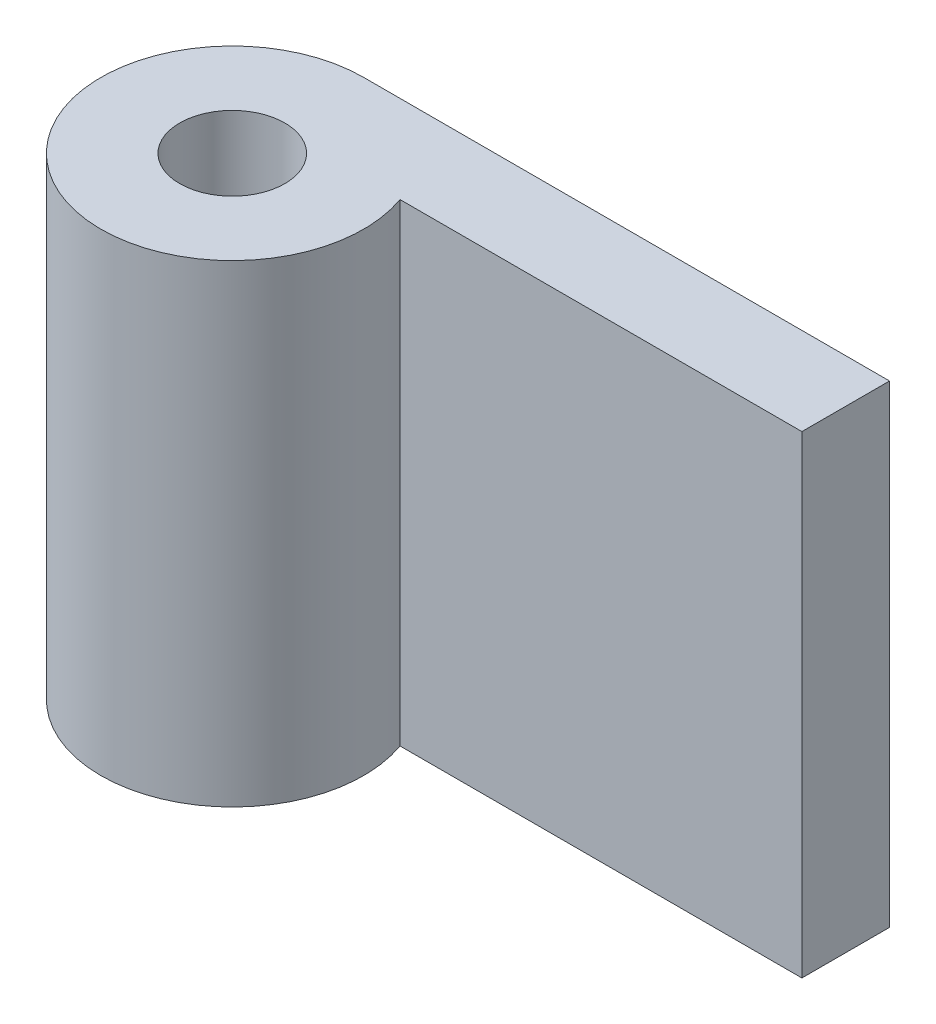
SolidWorks part; units mm, degrees
ref_plane "前视基准面" through (0, 0, 0) normal (0, 0, 1) x (1, 0, 0)
ref_plane "上视基准面" through (0, 0, 0) normal (0, 1, 0) x (1, 0, 0)
ref_plane "右视基准面" through (0, 0, 0) normal (1, 0, 0) x (0, 0, -1)
sketch "草图1" plane through (0, 0, 0) normal (0, 1, 0) x (1, 0, 0)
  circle A0 centre (0, 0) radius 3
  dimension "D1" = 6
extrude "凸台-拉伸1" add sketch "草图1" along normal blind 10.8
sketch "草图7" plane through (0, 0, 0) normal (1, 0, 0) x (0, 0, -1)
  line L0 (3, 10.8) -> (-3, 10.8) construction
  line L1 (1, 10.8) -> (3, 10.8)
  line L2 (1, 10.8) -> (1, 0)
  line L3 (1, 0) -> (3, 0)
  line L4 (3, 10.8) -> (3, 0)
  dimension "D1" = 2
extrude "凸台-拉伸2" add sketch "草图7" along normal blind 12
hole_wizard "ST2.2 间隙孔1" positions "3D草图4" profile "草图6" hole size "ST2.2" standard "GB"
sketch3d "3D草图4"
  line L0 (0, 10.8, 0) -> (0, 0, 0) construction
  point P7 (0, 10.8, 0)
sketch "草图6" plane through (0, 10.8, 0) normal (1, 0, 0) x (0, 0, 1)
  line L0 (0, 0) -> (0, 8.721)
  line L1 (0, 8.721) -> (1.2, 8)
  line L2 (1.2, 8) -> (1.2, 0)
  line L5 (1.2, 0) -> (0, 0)
  line L10 (0, 8.721) -> (-1.2, 8) construction
  line L11 (0, -6.35) -> (0, 107.95) construction
  dimension "孔直径" = 2.4
  dimension "孔深度" = 8
  dimension "导头角度" = 118
